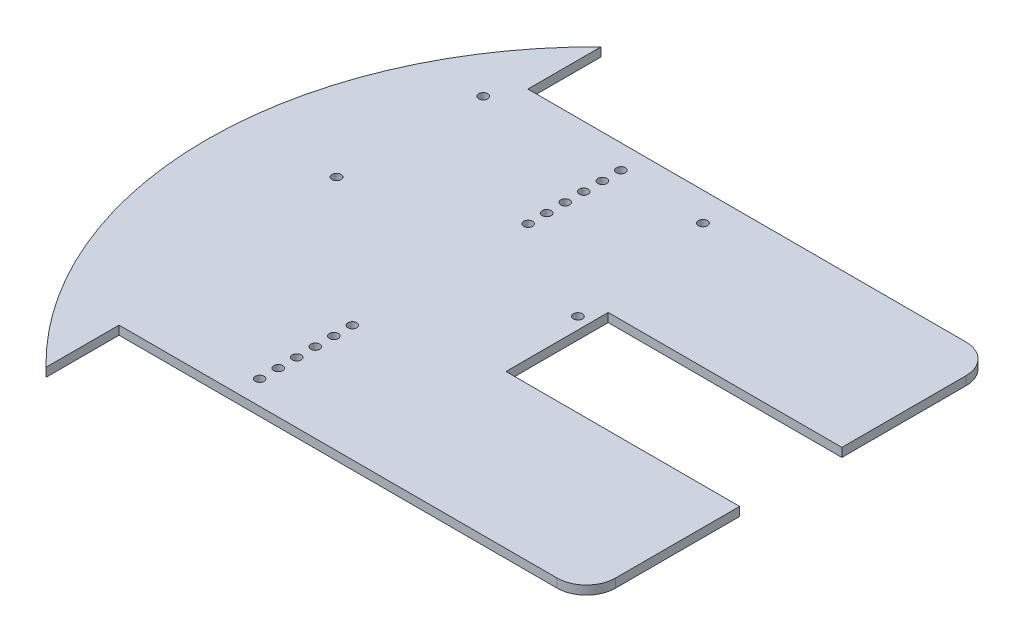
SolidWorks part; units mm, degrees
ref_plane "Front Plane" through (0, 0, 0) normal (0, 0, 1) x (1, 0, 0)
ref_plane "Top Plane" through (0, 0, 0) normal (0, 1, 0) x (1, 0, 0)
ref_plane "Right Plane" through (0, 0, 0) normal (1, 0, 0) x (0, 0, -1)
ref_plane "Plane1" through (0, 3, 0) normal (0, 1, 0) x (1, 0, 0)
sketch "Sketch1" plane through (0, 3, 0) normal (0, 1, 0) x (1, 0, 0)
  line L0 (200.3018, 35) -> (200.3018, 155)
  line L1 (190.3018, 165) -> (40.3018, 165)
  line L2 (40.3018, 165) -> (40.3018, 190)
  line L3 (40.3018, 0) -> (40.3018, 25)
  line L4 (40.3018, 25) -> (190.3018, 25)
  arc A0 (200.3018, 155) -> (190.3018, 165) centre (190.3018, 155) ccw
  arc A1 (40.3018, 190) -> (40.3018, 0) centre (133.1143, 95) ccw
  arc A2 (190.3018, 25) -> (200.3018, 35) centre (190.3018, 35) ccw
  circle A3 centre (80.3018, 33.16) radius 1.525
  circle A4 centre (80.3018, 125.09) radius 1.525
  circle A5 centre (80.3018, 131.44) radius 1.525
  circle A6 centre (80.3018, 137.79) radius 1.525
  circle A7 centre (80.3018, 64.91) radius 1.525
  circle A8 centre (80.3018, 156.84) radius 1.525
  circle A9 centre (80.3018, 150.49) radius 1.525
  circle A10 centre (80.3018, 144.14) radius 1.525
  circle A11 centre (80.3018, 58.56) radius 1.525
  circle A12 centre (80.3018, 52.21) radius 1.525
  circle A13 centre (80.3018, 45.86) radius 1.525
  circle A14 centre (80.3018, 39.51) radius 1.525
extrude "Boss-Extrude1" add sketch "Sketch1" against normal blind 3
sketch "Sketch2" plane through (0, 3, 0) normal (0, 1, 0) x (1, 0, 0)
  line L0 (200.3018, 35) -> (200.3018, 155) construction
  line L1 (120.3018, 77.5) -> (200.3018, 77.5)
  line L2 (120.3018, 77.5) -> (120.3018, 112.5)
  line L3 (120.3018, 112.5) -> (200.3018, 112.5)
  line L4 (200.3018, 77.5) -> (200.3018, 112.5)
  point P4 (200.3018, 95)
  point P7 (200.3018, 95)
  dimension "D1" = 35
  dimension "D2" = 80
extrude "Cut-Extrude1" cut sketch "Sketch2" against normal blind 5
sketch "Sketch4" plane through (0, 3, 0) normal (0, 1, 0) x (1, 0, 0)
  circle A0 centre (34.8193, 155.2) radius 1.55
  circle A1 centre (33.6193, 106.15) radius 1.55
  circle A2 centre (110.0193, 155.2) radius 1.55
  circle A3 centre (116.2693, 106.15) radius 1.55
extrude "Cut-Extrude2" cut sketch "Sketch4" against normal through all
